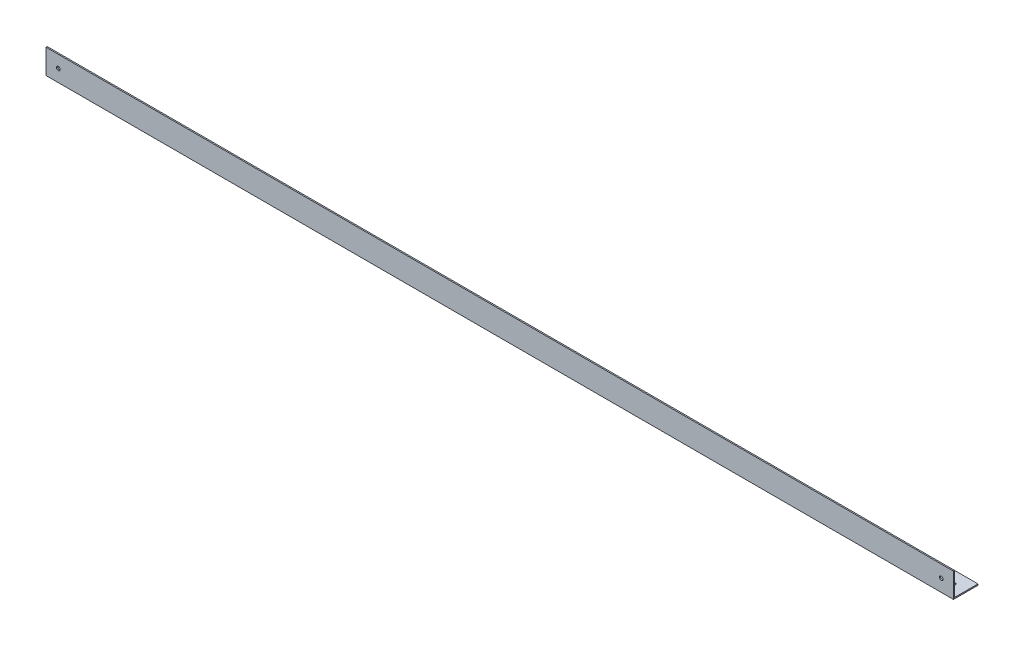
SolidWorks part; units mm, degrees
ref_plane "Front Plane" through (0, 0, 0) normal (0, 0, 1) x (1, 0, 0)
ref_plane "Top Plane" through (0, 0, 0) normal (0, 1, 0) x (1, 0, 0)
ref_plane "Right Plane" through (0, 0, 0) normal (1, 0, 0) x (0, 0, -1)
sketch "Sketch1" plane through (0, 0, 0) normal (1, 0, 0) x (0, 0, -1)
  line L0 (0, 0) -> (0, 20)
  line L1 (0, 20) -> (1, 20)
  line L2 (1, 20) -> (1, 1)
  line L3 (1, 1) -> (20, 1)
  line L4 (20, 1) -> (20, 0)
  line L5 (20, 0) -> (0, 0)
  dimension "D1" = 1
  dimension "D2" = 20
  dimension "D3" = 20
extrude "Boss-Extrude1" add sketch "Sketch1" along normal blind 740
sketch "Sketch2" plane through (0, 0, 0) normal (0, 0, 1) x (1, 0, 0)
  line L0 (0, 20) -> (0, 0) construction
  line L1 (740, 20) -> (0, 20) construction
  line L2 (740, 20) -> (740, 0) construction
  line L3 (740, 0) -> (0, 0) construction
  circle A0 centre (10, 10) radius 1.5
  circle A1 centre (730, 10) radius 1.5
  dimension "D3" = 3
  dimension "D4" = 3
  dimension "D1" = 10
  dimension "D2" = 10
  dimension "D5" = 10
  dimension "D6" = 10
extrude "Cut-Extrude1" cut sketch "Sketch2" against normal up to next
sketch "Sketch3" plane through (0, 0, 0) normal (0, -1, 0) x (1, 0, 0)
  line L0 (740, -20) -> (0, -20) construction
  line L1 (0, 0) -> (0, -20) construction
  line L2 (740, 0) -> (740, -20) construction
  circle A0 centre (10, -10) radius 1.5
  circle A1 centre (730, -10) radius 1.5
  dimension "D1" = 3
  dimension "D2" = 10
  dimension "D3" = 10
  dimension "D4" = 10
extrude "Cut-Extrude2" cut sketch "Sketch3" against normal up to next
